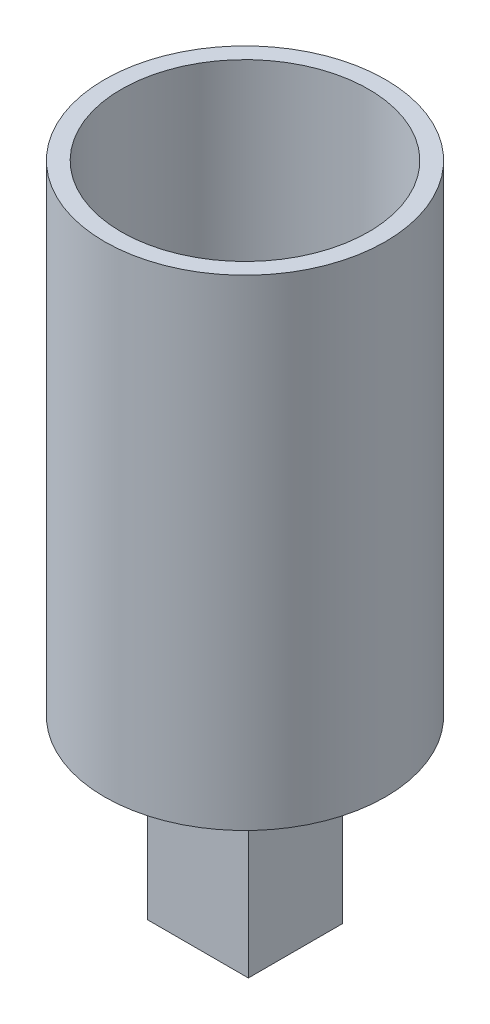
SolidWorks part; units mm, degrees
ref_plane "Front Plane" through (0, 0, 0) normal (0, 0, 1) x (1, 0, 0)
ref_plane "Top Plane" through (0, 0, 0) normal (0, 1, 0) x (1, 0, 0)
ref_plane "Right Plane" through (0, 0, 0) normal (1, 0, 0) x (0, 0, -1)
sketch "Sketch3" plane through (0, 0, 0) normal (0, 1, 0) x (-1, 0, 0)
  arc A0 (-34.2012, -13.4912) -> (33.5938, -14.9397) centre (0, 0) ccw
  arc A1 (-7.4141, 41.1027) -> (-38.8525, -15.326) centre (0, 0) ccw
  arc A3 (-34.7837, 11.9094) -> (-34.2012, -13.4912) centre (0, 0) ccw
  arc A4 (-38.8525, -15.326) -> (37.2374, 18.9149) centre (0, 0) ccw
  circle A5 centre (0, 0) radius 36.766 construction
  circle A6 centre (0, 0) radius 41.766 construction
  arc A7 (37.2374, 18.9149) -> (-7.4141, 41.1027) centre (0, 0) ccw
  arc A8 (33.5938, -14.9397) -> (-34.7837, 11.9094) centre (0, 0) ccw
  point P5 (37, 0)
  point P17 (30.6018, 9.3559)
  dimension "D2" = 5
extrude "Boss-Extrude2" add sketch "Sketch3" along normal up to surface (142.995 mm away)
sketch "Sketch4" plane through (0, -142.995, 0) normal (0, -1, 0) x (1, 0, 0)
  arc A1 (0, 36.766) -> (33.5938, -14.9397) centre (0, 0) ccw
  circle A2 centre (0, 0) radius 36.766 construction
  arc A3 (33.5938, -14.9397) -> (0, 36.766) centre (0, 0) ccw
extrude "Boss-Extrude3" add sketch "Sketch4" against normal blind 5
sketch "Sketch5" plane through (0, -142.995, 0) normal (0, -1, 0) x (1, 0, 0)
  line L0 (6, -6) -> (6, 6)
  line L1 (6, -6) -> (-6, -6)
  line L2 (6, 6) -> (-6, 6)
  line L3 (-6, -6) -> (-6, 6)
  line L4 (6, -6) -> (-6, 6) construction
  line L5 (6, 6) -> (-6, -6) construction
  point P1 (0, 0)
  dimension "D1" = 12
  dimension "D2" = 12
extrude "Cut-Extrude2" cut sketch "Sketch5" against normal up to next
sketch "Sketch6" plane through (0, -142.995, 0) normal (0, -1, 0) x (1, 0, 0)
  line L0 (10, -9) -> (10, 9)
  line L1 (10, -9) -> (-10, -9)
  line L2 (10, 9) -> (-10, 9)
  line L3 (-10, -9) -> (-10, 9)
  line L4 (10, -9) -> (-10, 9) construction
  line L5 (10, 9) -> (-10, -9) construction
  line L6 (-15, -14) -> (-15, 14)
  line L7 (15, 14) -> (-15, 14)
  line L8 (15, -14) -> (15, 14)
  line L9 (15, -14) -> (-15, -14)
  point P1 (0, 0)
  dimension "D2" = 18
  dimension "D3" = 20
  dimension "D1" = 5
extrude "Boss-Extrude4" add sketch "Sketch6" along normal blind 53
